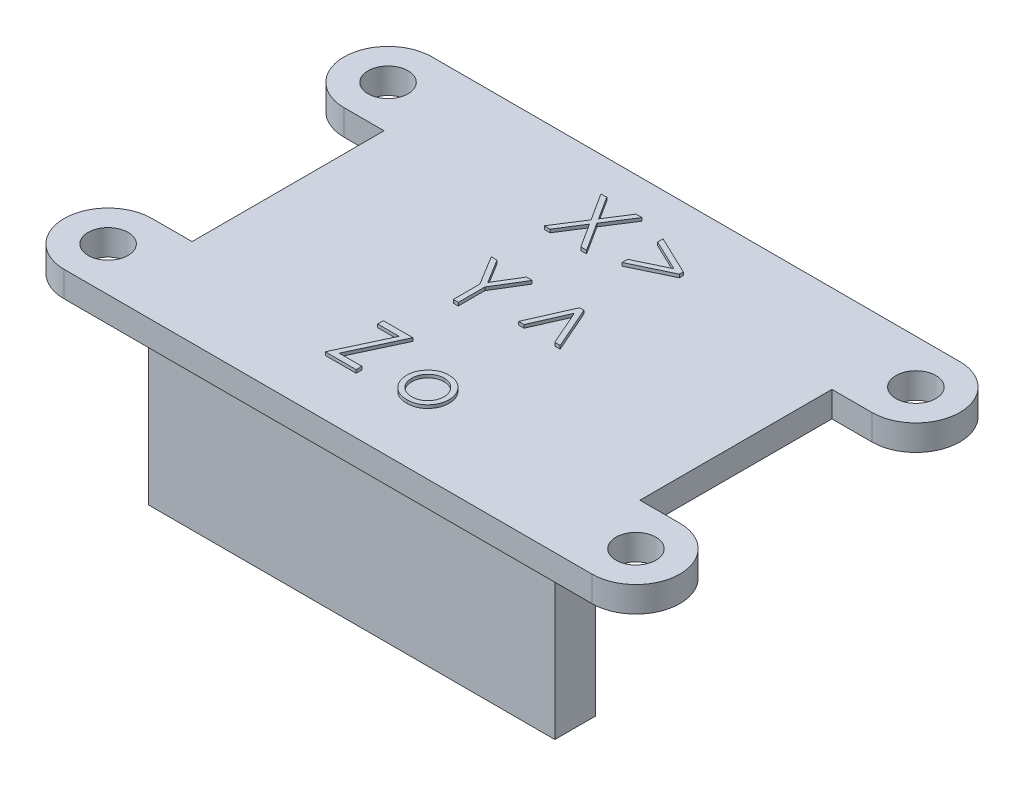
SolidWorks part; units mm, degrees
ref_plane "Front Plane" through (0, 0, 0) normal (0, 0, 1) x (1, 0, 0)
ref_plane "Top Plane" through (0, 0, 0) normal (0, 1, 0) x (1, 0, 0)
ref_plane "Right Plane" through (0, 0, 0) normal (1, 0, 0) x (0, 0, -1)
sketch "Sketch1" plane through (0, 0, 0) normal (0, 1, 0) x (1, 0, 0)
  line L0 (-14, 11.5) -> (-16.5, 11.5)
  line L1 (-14, -11.5) -> (14, -11.5)
  line L2 (-14, -11.5) -> (-14, 11.5) construction
  line L3 (-14, 11.5) -> (14, 11.5)
  line L4 (14, -11.5) -> (14, 11.5) construction
  line L5 (-14, -11.5) -> (14, 11.5) construction
  line L6 (-14, 11.5) -> (14, -11.5) construction
  line L7 (-14, -11.5) -> (-16.5, -11.5)
  line L8 (14, -11.5) -> (16.5, -11.5)
  line L9 (14, 11.5) -> (16.5, 11.5)
  line L10 (-14, 0) -> (14, 0) construction
  line L11 (-14, 6) -> (-14, -6)
  line L12 (14, 6) -> (14, -6)
  line L13 (0, 11.5) -> (0, -11.5) construction
  line L14 (14, 6) -> (16.5, 6)
  line L15 (-14, -6) -> (-16.5, -6)
  line L16 (-14, 6) -> (-16.5, 6)
  line L17 (16.5, -8.75) -> (-16.5, -8.75) construction
  line L18 (16.5, -8.75) -> (16.5, 8.75) construction
  line L19 (16.5, 8.75) -> (-16.5, 8.75) construction
  line L20 (-16.5, -8.75) -> (-16.5, 8.75) construction
  line L21 (16.5, -8.75) -> (-16.5, 8.75) construction
  line L22 (16.5, 8.75) -> (-16.5, -8.75) construction
  line L24 (14, -6) -> (16.5, -6)
  arc A0 (-16.5, 11.5) -> (-16.5, 6) centre (-16.5, 8.75) ccw
  arc A1 (16.5, 11.5) -> (16.5, 6) centre (16.5, 8.75) cw
  arc A2 (-16.5, -11.5) -> (-16.5, -6) centre (-16.5, -8.75) cw
  arc A3 (16.5, -11.5) -> (16.5, -6) centre (16.5, -8.75) ccw
  point P0 (0, 0)
  point P17 (0, 0)
  point P28 (-14, 0)
  point P31 (14, 0)
  dimension "D1" = 23
  dimension "D2" = 28
  dimension "D3" = 17.5
  dimension "D5" = 33
extrude "Boss-Extrude1" add sketch "Sketch1" along normal blind 1.6
sketch "Sketch2" plane through (0, 1.6, 0) normal (0, 1, 0) x (1, 0, 0)
  circle A0 centre (-16.5, 8.75) radius 1.25
  circle A1 centre (16.5, 8.75) radius 1.25
  circle A2 centre (16.5, -8.75) radius 1.25
  circle A3 centre (-16.5, -8.75) radius 1.25
  dimension "D1" = 2.5
extrude "Cut-Extrude1" cut sketch "Sketch2" against normal through all
sketch "Sketch3" plane through (0, 0, 0) normal (0, -1, 0) x (1, 0, 0)
  line L0 (0, 11.5) -> (0, -11.5) construction
  line L1 (-16.5, 11.5) -> (16.5, 11.5) construction
  line L2 (16.5, -11.5) -> (-16.5, -11.5) construction
  line L3 (-16.5, 8.75) -> (16.5, 8.75) construction
  line L4 (-12.7, 7.48) -> (12.7, 7.48)
  line L5 (-12.7, 7.48) -> (-12.7, 10.02)
  line L6 (-12.7, 10.02) -> (12.7, 10.02)
  line L7 (12.7, 7.48) -> (12.7, 10.02)
  line L8 (-12.7, 7.48) -> (12.7, 10.02) construction
  line L9 (-12.7, 10.02) -> (12.7, 7.48) construction
  point P6 (0, 8.75)
  dimension "D1" = 2.54
  dimension "D2" = 25.4
extrude "Boss-Extrude2" add sketch "Sketch3" along normal blind 10
sketch "Sketch4" plane through (0, 1.6, 0) normal (0, 1, 0) x (1, 0, 0)
  text T0 "X >\r\nY ^\r\nZ o"
extrude "Boss-Extrude3" add sketch "Sketch4" along normal blind 0.2
